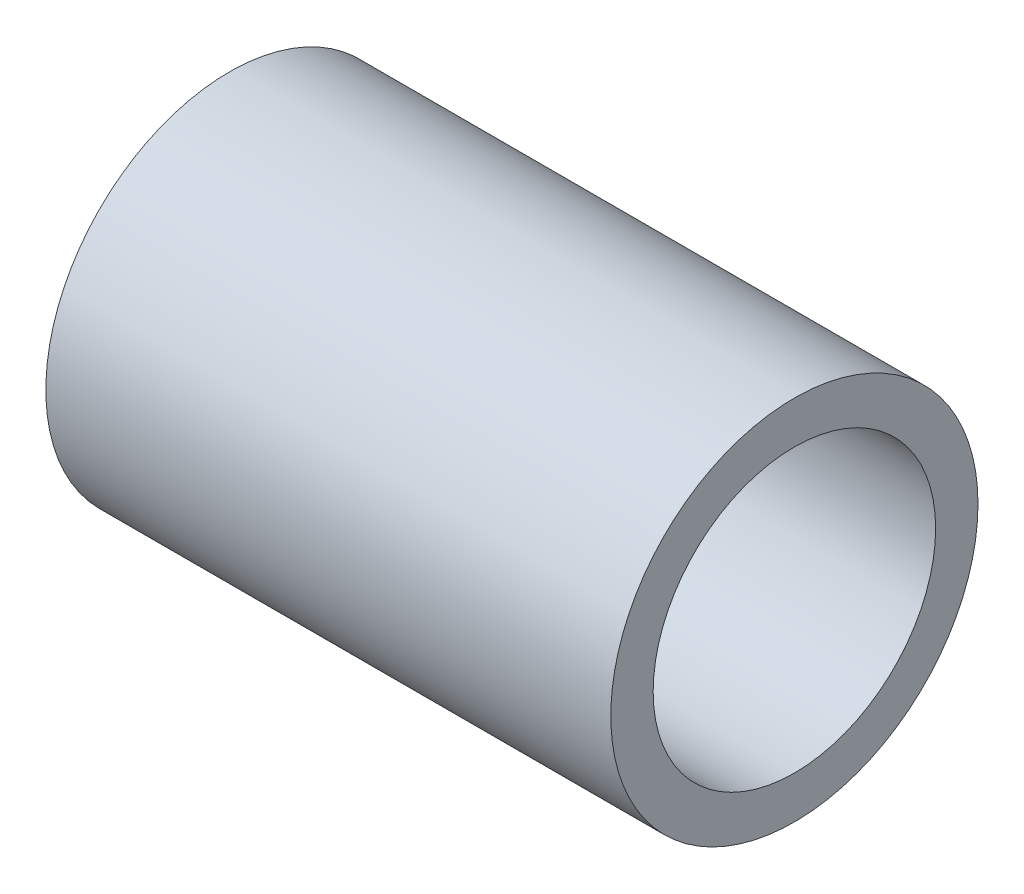
SolidWorks part; units mm, degrees
material "Copper"
ref_plane "Front Plane" through (0, 0, 0) normal (0, 0, 1) x (1, 0, 0)
ref_plane "Top Plane" through (0, 0, 0) normal (0, 1, 0) x (1, 0, 0)
ref_plane "Right Plane" through (0, 0, 0) normal (1, 0, 0) x (0, 0, -1)
sketch "Sketch1" plane through (0, 0, 0) normal (1, 0, 0) x (0, 0, -1)
  circle A0 centre (0, 0) radius 6.5
  circle A1 centre (0, 0) radius 5
  dimension "D1" = 13
  dimension "D2" = 10
extrude "Boss-Extrude1" add sketch "Sketch1" along normal blind 20
